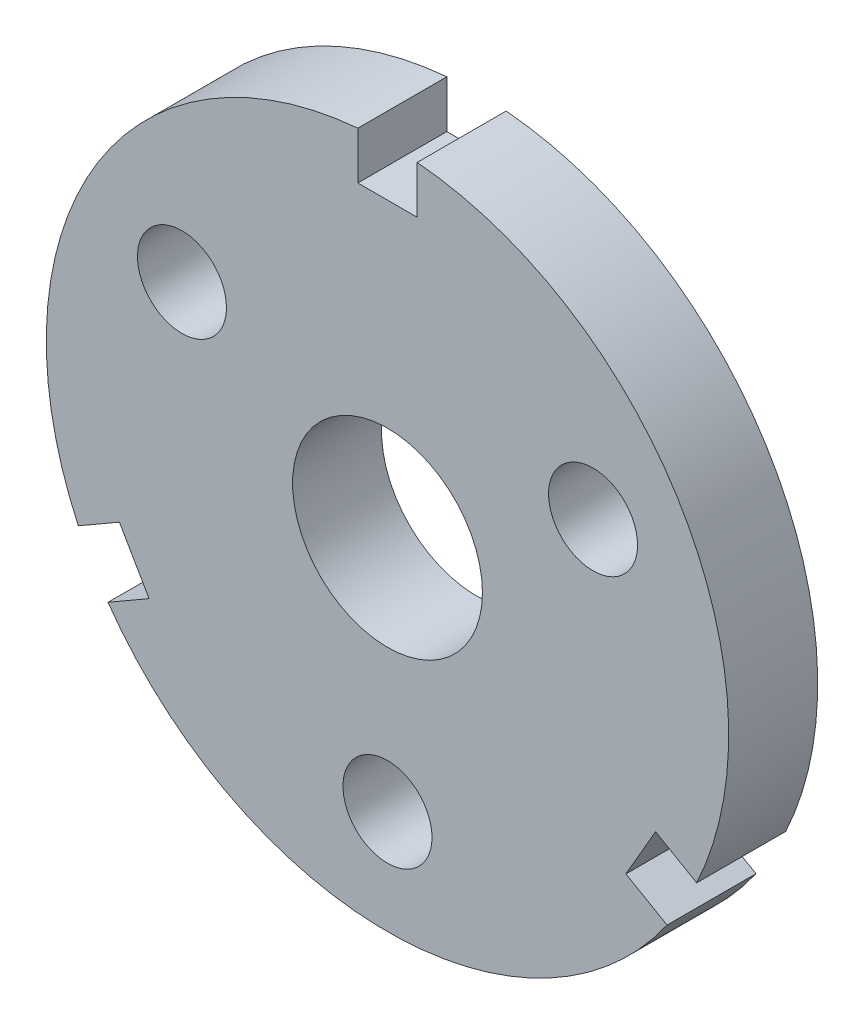
SolidWorks part; units mm, degrees
ref_plane "Front Plane" through (0, 0, 0) normal (0, 0, 1) x (1, 0, 0)
ref_plane "Top Plane" through (0, 0, 0) normal (0, 1, 0) x (1, 0, 0)
ref_plane "Right Plane" through (0, 0, 0) normal (1, 0, 0) x (0, 0, -1)
sketch "Sketch1" plane through (0, 0, 0) normal (0, 0, 1) x (1, 0, 0)
  line L0 (0, 0) -> (0, 63.2053) construction
  line L1 (5, 57.2822) -> (5, 49.2822)
  line L2 (5, 49.2822) -> (-5, 49.2822)
  line L3 (-5, 49.2822) -> (-5, 57.2822)
  line L6 (45.1796, -20.311) -> (52.1078, -24.311)
  line L7 (40.1796, -28.9712) -> (45.1796, -20.311)
  line L8 (47.1078, -32.9712) -> (40.1796, -28.9712)
  line L10 (-40.1796, -28.9712) -> (-47.1078, -32.9712)
  line L11 (-45.1796, -20.311) -> (-40.1796, -28.9712)
  line L12 (-52.1078, -24.311) -> (-45.1796, -20.311)
  line L17 (-47.1078, -32.9712) -> (-52.1078, -24.311) construction
  circle A0 centre (0, 0) radius 16
  circle A1 centre (0, 0) radius 40 construction
  arc A2 (-47.1078, -32.9712) -> (47.1078, -32.9712) centre (0, 0) ccw
  circle A3 centre (0, -40) radius 7.5
  circle A4 centre (-34.641, 20) radius 7.5
  circle A5 centre (34.641, 20) radius 7.5
  arc A6 (52.1078, -24.311) -> (5, 57.2822) centre (0, 0) ccw
  arc A7 (-5, 57.2822) -> (-52.1078, -24.311) centre (0, 0) ccw
  point P15 (0, 0)
  point P28 (0, 0)
  dimension "D1" = 32
  dimension "D2" = 80
  dimension "D3" = 115
  dimension "D4" = 15
  dimension "D6" = 8
  dimension "D7" = 10
  dimension "D5" = 3
  dimension "D8" = 3
extrude "Boss-Extrude1" add sketch "Sketch1" along normal blind 15
